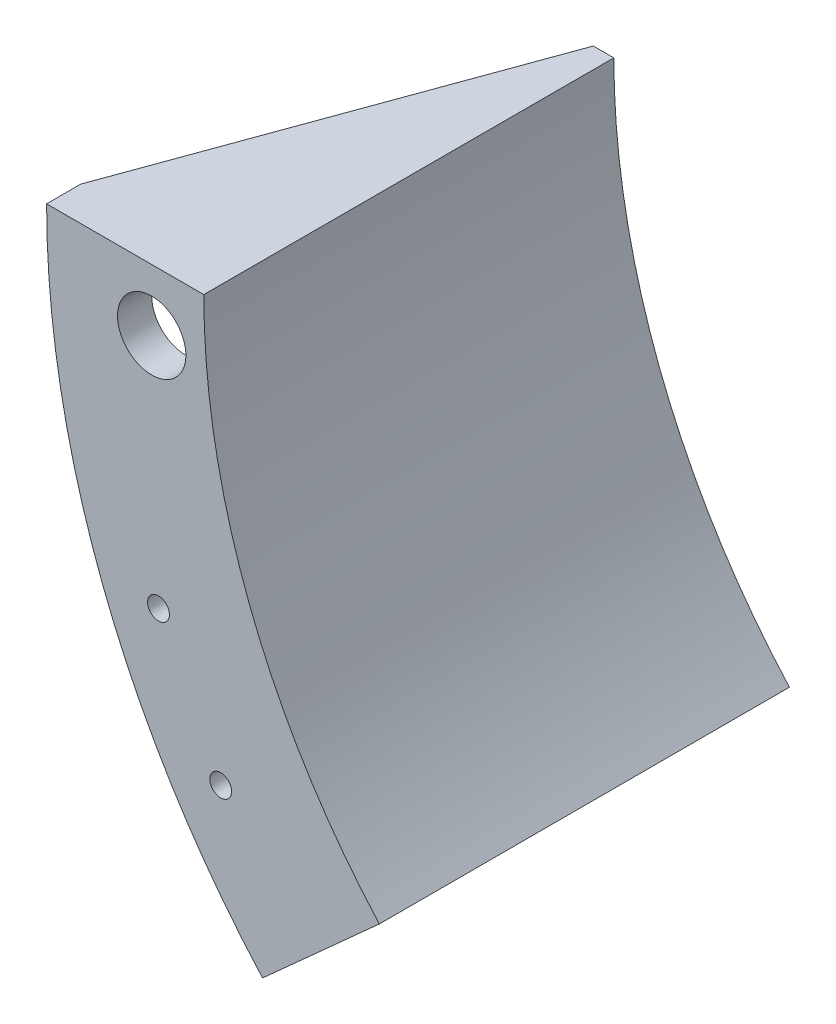
SolidWorks part; units mm, degrees
material "打印件"
ref_plane "前视基准面" through (0, 0, 0) normal (0, 0, 1) x (1, 0, 0)
ref_plane "上视基准面" through (0, 0, 0) normal (0, 1, 0) x (1, 0, 0)
ref_plane "右视基准面" through (0, 0, 0) normal (1, 0, 0) x (0, 0, -1)
sketch "草图1" plane through (0, 0, 0) normal (0, 0, 1) x (1, 0, 0)
  line L2 (-100, 0) -> (-103, 0)
  line L3 (-74.3145, -66.9131) -> (-76.5439, -68.9205)
  line L4 (-74.3145, -66.9131) -> (0, 0) construction
  arc A2 (-100, 0) -> (-74.3145, -66.9131) centre (0, 0) ccw
  arc A3 (-103, 0) -> (-76.5439, -68.9205) centre (0, 0) ccw
  dimension "D1" = 200
  dimension "D2" = 206
  dimension "D3" = 42
extrude "凸台-拉伸1" add sketch "草图1" along normal blind 60
sketch "草图2" plane through (0, 0, 60) normal (0, 0, 1) x (1, 0, 0)
  line L4 (-75.3351, -67.832) -> (-91.4068, -82.3031)
  line L5 (-101.3734, 0) -> (-123, 0)
  line L6 (-76.5439, -68.9205) -> (-74.3145, -66.9131) construction
  arc A2 (-123, 0) -> (-91.4068, -82.3031) centre (0, 0) ccw
  arc A3 (-101.3734, 0) -> (-75.3351, -67.832) centre (0, 0) ccw
  dimension "D1" = 246
extrude "凸台-拉伸2" add sketch "草图2" against normal blind 5
sketch "草图4" plane through (0, 0, 55) normal (0, 0, -1) x (-1, 0, 0)
  line L0 (97.5255, -60.9407) -> (0, 0) construction
  line L1 (0, 0) -> (106.6261, -43.0798) construction
  line L2 (91.4068, -82.3031) -> (76.5439, -68.9205) construction
  circle A0 centre (97.5255, -60.9407) radius 1.6
  circle A1 centre (106.6261, -43.0798) radius 1.6
  circle A2 centre (0, 0) radius 115 construction
  dimension "D1" = 3.2
  dimension "D2" = 3.2
  dimension "D3" = 10
  dimension "D4" = 230
  dimension "D5" = 10
extrude "切除-拉伸1" cut sketch "草图4" against normal through all
sketch "草图5" plane through (0, 0, 0) normal (0, 1, 0) x (1, 0, 0)
  line L0 (-103, 0) -> (-123, -55)
  line L1 (-123, -55) -> (-100, -55)
  line L2 (-100, -60) -> (-100, 0) construction
  line L3 (-100, -55) -> (-100, 0)
  line L4 (-100, 0) -> (-103, 0)
extrude "凸台-拉伸3" add sketch "草图5" against normal blind 4
sketch "草图6" plane through (0, 0, 0) normal (0.6691, -0.7431, 0) x (0, 0, -1)
  line L0 (-55, -123) -> (0, -103)
  line L1 (0, -103) -> (0, -100)
  line L2 (0, -100) -> (-55, -100)
  line L3 (-60, -100) -> (0, -100) construction
  line L4 (-55, -123) -> (-55, -94.035) construction
  line L5 (-55, -100) -> (-55, -123)
  point P4 (0, 0)
extrude "凸台-拉伸4" add sketch "草图6" against normal blind 4
sketch "草图7" plane through (0, 0, 55) normal (0, 0, -1) x (-1, 0, 0)
  line L4 (122.9349, -4) -> (102.9223, -4) construction
  circle A1 centre (107.6243, -9) radius 5
  arc A2 (79.1627, -65.8959) -> (102.9223, -4) centre (0, 0) ccw construction
  point P5 (106.312, -19.0201)
  dimension "D1" = 10
extrude "切除-拉伸2" cut sketch "草图7" against normal through all
